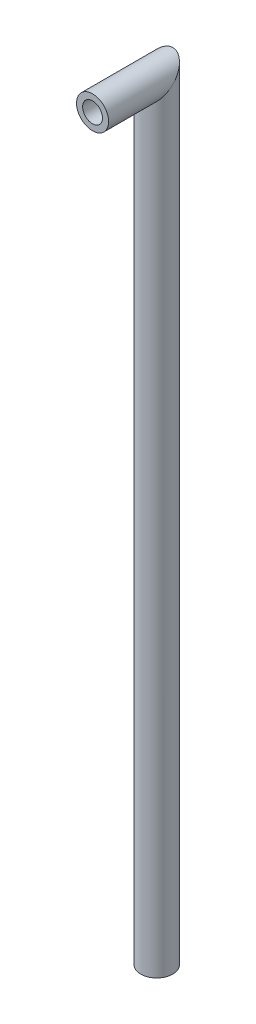
SolidWorks part; units mm, degrees
material "Custom Plastic"
ref_plane "Front Plane" through (0, 0, 0) normal (0, 0, 1) x (1, 0, 0)
ref_plane "Top Plane" through (0, 0, 0) normal (0, 1, 0) x (1, 0, 0)
ref_plane "Right Plane" through (0, 0, 0) normal (1, 0, 0) x (0, 0, -1)
sketch "Sketch1" plane through (0, 0, 0) normal (0, 0, 1) x (1, 0, 0)
  circle A0 centre (0, 0) radius 5
  dimension "D1" = 10
sketch3d "3DSketch1"
  line L0 (0, 0, 0) -> (0, 0, -20)
  line L1 (0, 0, -20) -> (0, -240, -20)
  dimension "D1" = 20
  dimension "D2" = 240
sweep "Sweep1" add profiles "Sketch1" path "3DSketch1"
sketch "Sketch2" plane through (0, 0, 0) normal (0, 0, 1) x (1, 0, 0)
  circle A0 centre (0, 0) radius 3.1
  dimension "D1" = 6.2
extrude "Cut-Extrude1" cut sketch "Sketch2" against normal blind 15
ref_plane "Plane1" through (0, 0, -15) normal (0, 0, 1) x (1, 0, 0)
sketch "Sketch4" plane through (0, 0, -15) normal (0, 0, 1) x (1, 0, 0)
  line L0 (-1.6882, -2.6) -> (1.6882, -2.6)
  line L1 (1.6882, -2.6) -> (1.6882, -3.6)
  line L2 (1.6882, -3.6) -> (-1.6882, -3.6)
  line L3 (-1.6882, -3.6) -> (-1.6882, -2.6)
  circle A0 centre (0, 0) radius 3.1 construction
  circle A1 centre (0, 0) radius 3.1 construction
  dimension "D1" = 2.6
  dimension "D2" = 1
extrude "Boss-Extrude1" add sketch "Sketch4" along normal blind 9
sketch "Sketch5" plane through (0, -240, 0) normal (0, -1, 0) x (1, 0, 0)
  circle A0 centre (0, -20) radius 3.1
  dimension "D1" = 6.2
extrude "Cut-Extrude2" cut sketch "Sketch5" against normal blind 240
